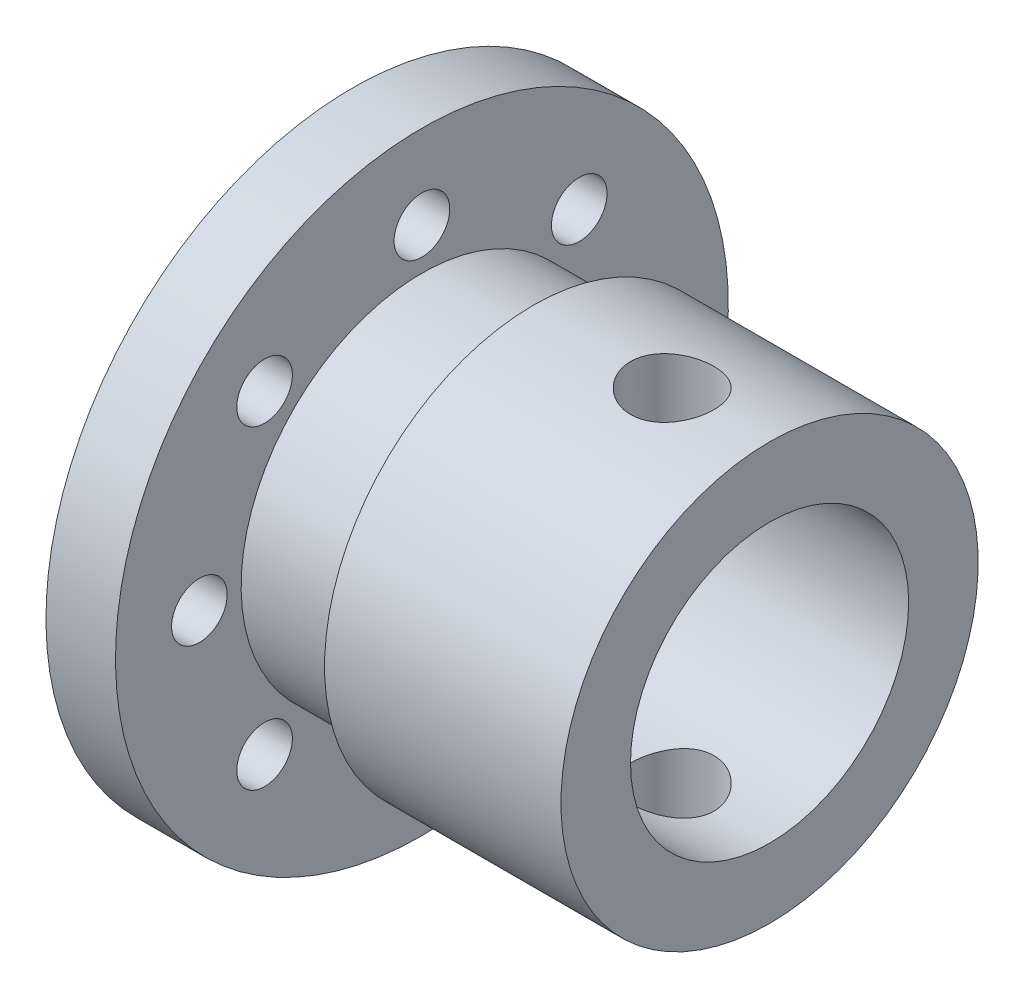
SolidWorks part; units mm, degrees
ref_plane "Front Plane" through (0, 0, 0) normal (0, 0, 1) x (1, 0, 0)
ref_plane "Top Plane" through (0, 0, 0) normal (0, 1, 0) x (1, 0, 0)
ref_plane "Right Plane" through (0, 0, 0) normal (1, 0, 0) x (0, 0, -1)
sketch "Sketch2" plane through (0, 0, 0) normal (0, 0, 1) x (1, 0, 0)
  line L0 (542.9168, 0) -> (561.8289, 0) construction
  line L3 (560.6509, 5) -> (560.6509, 7.5)
  line L4 (560.6509, 7.5) -> (552.1509, 7.5)
  line L6 (545.6509, 5) -> (560.6509, 5)
  line L7 (548.1509, 7.5) -> (548.1509, 6.5)
  line L9 (548.1509, 7.5) -> (548.1509, 11.0166)
  line L10 (548.1509, 11.0166) -> (545.6509, 11.0166)
  line L11 (545.6509, 11.0166) -> (545.6509, 5)
  line L12 (548.1509, 6.5) -> (552.1509, 6.5)
  line L13 (552.1509, 6.5) -> (552.1509, 7.5)
  dimension "D1" = 2.5
  dimension "D2" = 7.5
  dimension "D3" = 15
  dimension "D4" = 2.5
  dimension "D5" = 1
  dimension "D6" = 4
revolve "Revolve1" add sketch "Sketch2" angle 360 about L0
sketch "Sketch3" plane through (0, 0, 0) normal (0, 1, 0) x (1, 0, 0)
  line L0 (548.1509, 0) -> (560.6509, 0) construction
  line L1 (548.1509, -11.0166) -> (548.1509, 11.0166) construction
  line L2 (560.6509, 24.4344) -> (560.6509, -15.4312) construction
  circle A0 centre (557.1509, 0) radius 1.5
  dimension "D1" = 3
  dimension "D2" = 3.5
extrude "Cut-Extrude1" cut sketch "Sketch3" against normal through all both and the other way through all
sketch "Sketch13" plane through (548.1509, 0, 0) normal (1, 0, 0) x (0, 0, -1)
  circle A0 centre (0, 8) radius 1
  circle A1 centre (5.6569, 5.6569) radius 1
  circle A2 centre (8, 0) radius 1
  circle A3 centre (5.6569, -5.6569) radius 1
  circle A4 centre (0, -8) radius 1
  circle A5 centre (-5.6569, -5.6569) radius 1
  circle A6 centre (-8, 0) radius 1
  circle A7 centre (-5.6569, 5.6569) radius 1
  point P20 (0, 0)
  dimension "D1" = 2
  dimension "D2" = 8
  dimension "D3" = 8
extrude "Cut-Extrude2" cut sketch "Sketch13" against normal through all
